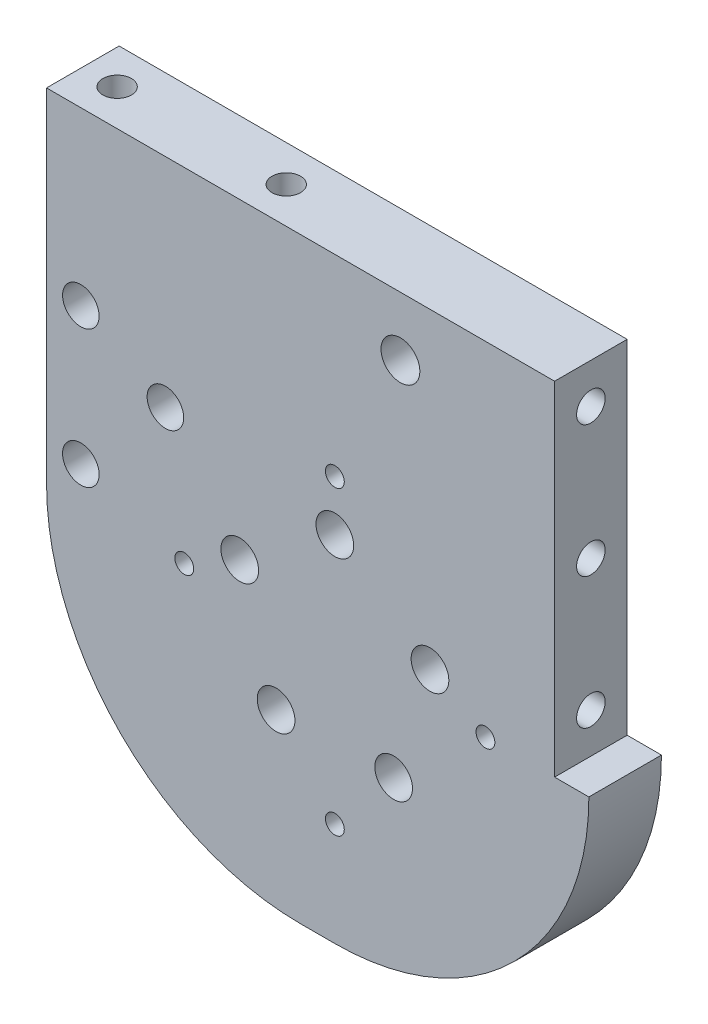
SolidWorks part; units mm, degrees
material "6061 Alloy"
ref_plane "Front" through (0, 0, 0) normal (0, 0, 1) x (1, 0, 0)
ref_plane "Top" through (0, 0, 0) normal (0, 1, 0) x (1, 0, 0)
ref_plane "Right" through (0, 0, 0) normal (1, 0, 0) x (0, 0, -1)
ref_plane "Plane1" through (0, 0, 0) normal (0, 0, -1) x (-1, 0, 0)
sketch "Sketch1" plane through (0, 0, 0) normal (0, 0, -1) x (-1, 0, 0)
  line L0 (-6, -44.45) -> (44.45, -44.45)
  line L1 (44.45, -44.45) -> (44.45, 60)
  line L2 (44.45, 60) -> (-44.45, 60)
  line L3 (-44.45, 60) -> (-44.45, 0)
  line L4 (-44.45, 0) -> (-50.45, 0)
  arc A0 (-50.45, 0) -> (-6, -44.45) centre (-6, 0) ccw
extrude "Boss-Extrude1" add sketch "Sketch1" against normal blind 12.7
hole_wizard "M4x0.7 Tapped Hole1" positions "Sketch3" profile "Sketch2" tap size "M4x0.7" standard "ANSI Metric" end condition through all
sketch "Sketch3" plane through (0, 0, 12.7) normal (0, 0, 1) x (1, 0, 0)
  point P0 (32.35, 0.009)
  point P1 (6, -26.35)
  point P2 (-20.35, -0.01)
  point P3 (6, 26.35)
sketch "Sketch2" plane through (32.35, 0.009, 12.7) normal (1, 0, 0) x (0, -1, 0)
  line L0 (0, 0) -> (0, 12.7)
  line L1 (0, 12.7) -> (1.65, 12.7)
  line L2 (1.65, 12.7) -> (1.65, 0)
  line L5 (1.65, 0) -> (0, 0)
  line L11 (0, -6.35) -> (0, 107.95) construction
  dimension "Thru Tap Drill Dia." = 3.3
  dimension "Thru Tap Drill Depth" = 12.7
hole_wizard "M8x1.25 Tapped Hole1" positions "Sketch5" profile "Sketch4" tap size "M8x1.25" standard "ANSI Metric" end condition through all
sketch "Sketch5" plane through (0, 0, 12.7) normal (0, 0, 1) x (1, 0, 0)
  point P0 (17.4725, 49.6929)
sketch "Sketch4" plane through (17.4725, 49.6929, 12.7) normal (1, 0, 0) x (0, -1, 0)
  line L0 (0, 0) -> (0, 12.7)
  line L1 (0, 12.7) -> (3.4, 12.7)
  line L2 (3.4, 12.7) -> (3.4, 0)
  line L5 (3.4, 0) -> (0, 0)
  line L11 (0, -6.35) -> (0, 107.95) construction
  dimension "Thru Tap Drill Dia." = 6.8
  dimension "Thru Tap Drill Depth" = 12.7
hole_wizard "CSK for M6 Flat Head Machine Screw1" positions "Sketch7" profile "Sketch6" countersink size "M6" standard "ANSI Metric" end condition through all
sketch "Sketch7" plane through (0, 0, 0) normal (0, 0, -1) x (-1, 0, 0)
  point P0 (23.65, 22)
sketch "Sketch6" plane through (-23.65, 22, 0) normal (1, 0, 0) x (0, 1, 0)
  line L0 (0, 0) -> (0, 12.7)
  line L1 (0, 12.7) -> (3.2, 12.7)
  line L2 (3.2, 12.7) -> (3.2, 3.1)
  line L3 (3.2, 3.1) -> (6.3, 0)
  line L5 (6.3, 0) -> (0, 0)
  line L6 (-3.2, 3.1) -> (-6.3, 0) construction
  line L11 (0, -6.35) -> (0, 107.95) construction
  dimension "Thru Hole Dia." = 6.4
  dimension "Thru Hole Depth" = 12.7
  dimension "Near C'Sink Dia." = 12.6
  dimension "Near C'Sink Angle" = 90
hole_wizard "M6x1.0 Tapped Hole2" positions "Sketch9" profile "Sketch8" tap size "M6x1.0" standard "ANSI Metric"
sketch "Sketch9" plane through (44.45, 0, 0) normal (1, 0, 0) x (0, 0, -1)
  point P0 (-6.35, 7)
  point P1 (-6.35, 53)
  point P2 (-6.35, 30)
sketch "Sketch8" plane through (44.45, 7, 6.35) normal (0, 1, 0) x (0, 0, -1)
  line L0 (0, 0) -> (0, 16.5022)
  line L1 (0, 16.5022) -> (2.5, 15)
  line L2 (2.5, 15) -> (2.5, 0)
  line L5 (2.5, 0) -> (0, 0)
  line L10 (0, 16.5022) -> (-2.5, 15) construction
  line L11 (0, -6.35) -> (0, 107.95) construction
  dimension "Tap Drill Dia." = 5
  dimension "Tap Drill Depth" = 15
  dimension "Drill Angle" = 118
hole_wizard "M6x1.0 Tapped Hole1" positions "Sketch11" profile "Sketch10" tap size "M6x1.0" standard "ANSI Metric"
sketch "Sketch11" plane through (0, 60, 0) normal (0, 1, 0) x (1, 0, 0)
  point P0 (-38.45, -6.35)
  point P1 (-8.85, -6.35)
sketch "Sketch10" plane through (-38.45, 60, 6.35) normal (1, 0, 0) x (0, 0, 1)
  line L0 (0, 0) -> (0, 16.5022)
  line L1 (0, 16.5022) -> (2.5, 15)
  line L2 (2.5, 15) -> (2.5, 0)
  line L5 (2.5, 0) -> (0, 0)
  line L10 (0, 16.5022) -> (-2.5, 15) construction
  line L11 (0, -6.35) -> (0, 107.95) construction
  dimension "Tap Drill Dia." = 5
  dimension "Tap Drill Depth" = 15
  dimension "Drill Angle" = 118
hole_wizard "CSK for M6 Flat Head Machine Screw2" positions "Sketch13" profile "Sketch12" countersink size "M6" standard "ANSI Metric" end condition through all
sketch "Sketch13" plane through (0, 0, 0) normal (0, 0, -1) x (-1, 0, 0)
  point P0 (38.45, 30)
  point P1 (38.45, 6)
sketch "Sketch12" plane through (-38.45, 30, 0) normal (1, 0, 0) x (0, 1, 0)
  line L0 (0, 0) -> (0, 12.7)
  line L1 (0, 12.7) -> (3.2, 12.7)
  line L2 (3.2, 12.7) -> (3.2, 3.1)
  line L3 (3.2, 3.1) -> (6.3, 0)
  line L5 (6.3, 0) -> (0, 0)
  line L6 (-3.2, 3.1) -> (-6.3, 0) construction
  line L11 (0, -6.35) -> (0, 107.95) construction
  dimension "Thru Hole Dia." = 6.4
  dimension "Thru Hole Depth" = 12.7
  dimension "Near C'Sink Dia." = 12.6
  dimension "Near C'Sink Angle" = 90
hole_wizard "1-3/4 Clearance Hole1" positions "Sketch15" profile "Sketch14" hole size "1-3/4" standard "ANSI Inch"
sketch "Sketch15" plane through (0, 0, 0) normal (0, 0, -1) x (-1, 0, 0)
  point P0 (-6, 0)
sketch "Sketch14" plane through (6, 0, 0) normal (1, 0, 0) x (0, 1, 0)
  line L0 (0, 0) -> (0, 5)
  line L1 (0, 5) -> (22.5, 5)
  line L2 (22.5, 5) -> (22.5, 0)
  line L5 (22.5, 0) -> (0, 0)
  line L10 (0, 5) -> (-22.5, 5) construction
  line L11 (0, -6.35) -> (0, 107.95) construction
  dimension "Hole Dia." = 45
  dimension "Hole Depth" = 5
  dimension "Drill Angle" = 180
hole_wizard "M6 Clearance Hole1" positions "Sketch17" profile "Sketch16" hole size "M6" standard "ANSI Metric" end condition through all
sketch "Sketch17" plane through (0, 0, 12.7) normal (0, 0, 1) x (1, 0, 0)
  point P0 (6, 17.5)
  point P1 (22.6435, 5.4078)
  point P2 (16.2862, -14.1578)
  point P3 (-4.2862, -14.1578)
  point P4 (-10.6435, 5.4078)
sketch "Sketch16" plane through (6, 17.5, 12.7) normal (1, 0, 0) x (0, -1, 0)
  line L0 (0, 0) -> (0, 12.7)
  line L1 (0, 12.7) -> (3.3, 12.7)
  line L2 (3.3, 12.7) -> (3.3, 0)
  line L5 (3.3, 0) -> (0, 0)
  line L11 (0, -6.35) -> (0, 107.95) construction
  dimension "Thru Hole Dia." = 6.6
  dimension "Thru Hole Depth" = 12.7
fillet "Fillet1" radius 44.45 1 edges at (-44.45, -44.45, 6.35)
